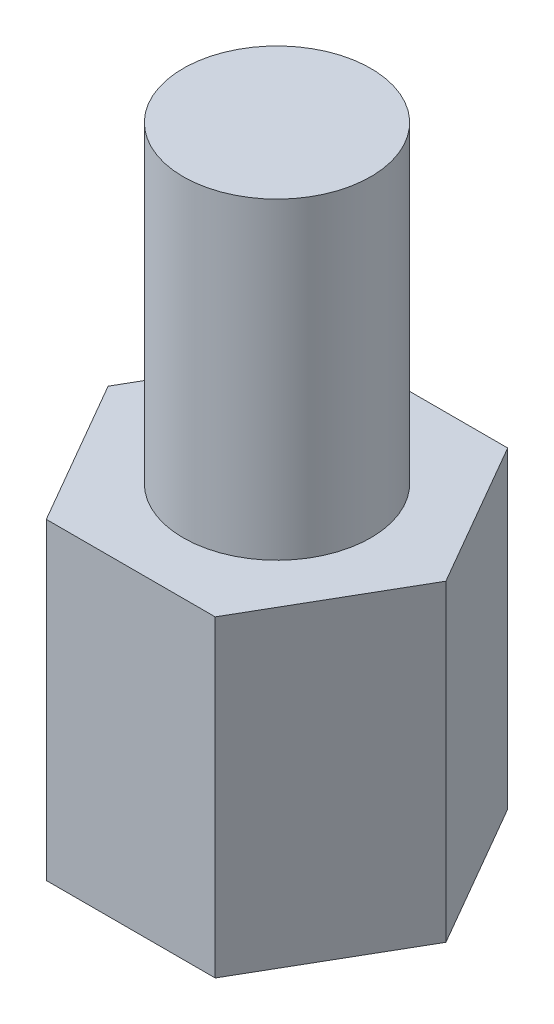
SolidWorks part; units mm, degrees
material "黄铜"
ref_plane "前视基准面" through (0, 0, 0) normal (0, 0, 1) x (1, 0, 0)
ref_plane "上视基准面" through (0, 0, 0) normal (0, 1, 0) x (1, 0, 0)
ref_plane "右视基准面" through (0, 0, 0) normal (1, 0, 0) x (0, 0, -1)
other "Configuration Table"
sketch "草图1" plane through (0, 0, 0) normal (0, 1, 0) x (1, 0, 0)
  line L4 (2.7, 0) -> (1.35, 2.3383)
  line L5 (1.35, 2.3383) -> (-1.35, 2.3383)
  line L6 (-1.35, 2.3383) -> (-2.7, 0)
  line L7 (-2.7, 0) -> (-1.35, -2.3383)
  line L8 (-1.35, -2.3383) -> (1.35, -2.3383)
  line L9 (1.35, -2.3383) -> (2.7, 0)
  circle A0 centre (0, 0) radius 2.3383 construction
  dimension "D1" = 2.7
extrude "凸台-拉伸1" add sketch "草图1" along normal blind 5
sketch "草图2" plane through (0, 0, 0) normal (0, 1, 0) x (1, 0, 0)
  circle A0 centre (0, 0) radius 1.5
extrude "凸台-拉伸2" add sketch "草图2" along normal blind 10
sketch "草图3" plane through (0, 0, 0) normal (0, 1, 0) x (1, 0, 0)
  circle A0 centre (0, 0) radius 1.5
extrude "切除-拉伸2" cut sketch "草图3" against normal blind 1 and the other way blind 5 contours A0
